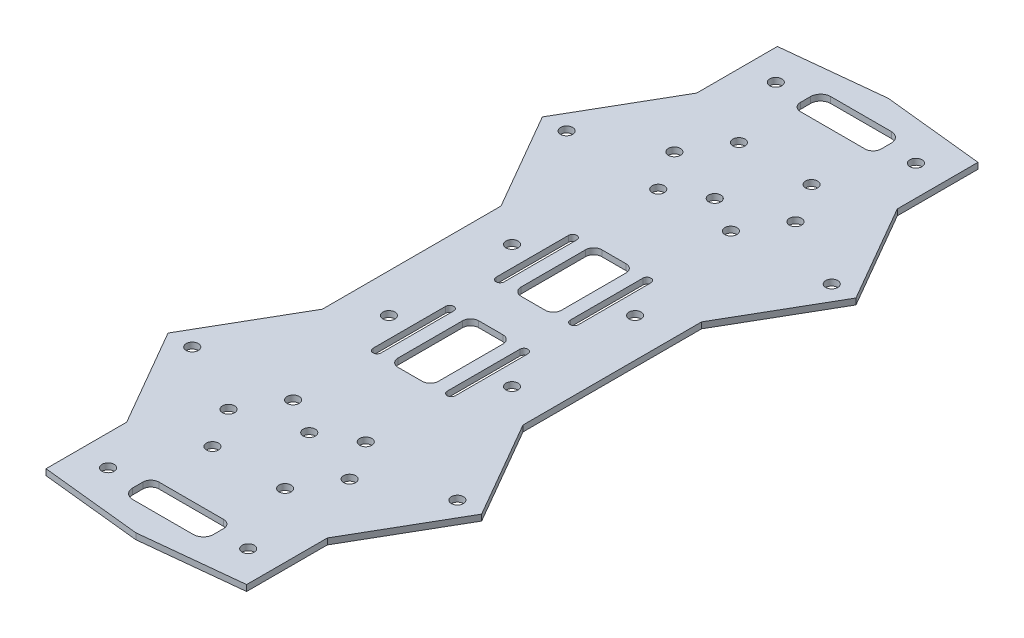
SolidWorks part; units mm, degrees
other "TopFrame"
ref_plane "Front Plane" through (0, 0, 0) normal (0, 0, 1) x (1, 0, 0)
ref_plane "Top Plane" through (0, 0, 0) normal (0, 1, 0) x (1, 0, 0)
ref_plane "Right Plane" through (0, 0, 0) normal (1, 0, 0) x (0, 0, -1)
sketch "Sketch1" plane through (0, 0, 0) normal (0, 1, 0) x (1, 0, 0)
  line L0 (-9.2, 6.25) -> (-9.2, 24.25) construction
  line L1 (-3, 5.25) -> (3, 5.25)
  line L2 (-5, 7.25) -> (-5, 23.25)
  line L3 (-3, 25.25) -> (3, 25.25)
  line L4 (5, 7.25) -> (5, 23.25)
  line L5 (-5, 5.25) -> (5, 25.25) construction
  line L6 (-5, 25.25) -> (5, 5.25) construction
  line L11 (-10.2, 6.25) -> (-10.2, 24.25)
  line L12 (-8.2, 6.25) -> (-8.2, 24.25)
  line L13 (0, 5.25) -> (0, 25.25) construction
  line L14 (9.2, 6.25) -> (9.2, 24.25) construction
  line L15 (10.2, 6.25) -> (10.2, 24.25)
  line L16 (8.2, 6.25) -> (8.2, 24.25)
  line L17 (-3, 0) -> (3, 0) construction
  line L18 (0, -5.25) -> (0, -25.25) construction
  line L19 (-5, -25.25) -> (5, -5.25) construction
  line L20 (-5, -5.25) -> (5, -25.25) construction
  line L21 (5, -7.25) -> (5, -23.25)
  line L22 (-3, -25.25) -> (3, -25.25)
  line L23 (-5, -7.25) -> (-5, -23.25)
  line L24 (-3, -5.25) -> (3, -5.25)
  line L25 (9.2, -6.25) -> (9.2, -24.25) construction
  line L26 (10.2, -6.25) -> (10.2, -24.25)
  line L27 (8.2, -6.25) -> (8.2, -24.25)
  line L28 (-9.2, -6.25) -> (-9.2, -24.25) construction
  line L29 (-10.2, -6.25) -> (-10.2, -24.25)
  line L30 (-8.2, -6.25) -> (-8.2, -24.25)
  line L31 (0, 93.25) -> (-24.863, 90.6368)
  line L32 (-24.863, 90.6368) -> (-24.863, 70.6368)
  line L33 (-24.863, 70.6368) -> (-38.863, 46.3881)
  line L34 (-38.863, 46.3881) -> (-24.863, 22.1394)
  line L35 (-24.863, 22.1394) -> (-24.863, -22.1394)
  line L36 (24.863, 22.1394) -> (24.863, -22.1394)
  line L37 (38.863, 46.3881) -> (24.863, 22.1394)
  line L38 (24.863, 70.6368) -> (38.863, 46.3881)
  line L39 (24.863, 90.6368) -> (24.863, 70.6368)
  line L40 (0, 93.25) -> (24.863, 90.6368)
  line L41 (0, -93.25) -> (24.863, -90.6368)
  line L42 (24.863, -90.6368) -> (24.863, -70.6368)
  line L43 (24.863, -70.6368) -> (38.863, -46.3881)
  line L44 (38.863, -46.3881) -> (24.863, -22.1394)
  line L45 (-38.863, -46.3881) -> (-24.863, -22.1394)
  line L46 (-24.863, -70.6368) -> (-38.863, -46.3881)
  line L47 (-24.863, -90.6368) -> (-24.863, -70.6368)
  line L48 (0, -93.25) -> (-24.863, -90.6368)
  arc A0 (-3, 5.25) -> (-5, 7.25) centre (-3, 7.25) cw
  arc A1 (3, 5.25) -> (5, 7.25) centre (3, 7.25) ccw
  arc A2 (3, 25.25) -> (5, 23.25) centre (3, 23.25) cw
  arc A3 (-5, 23.25) -> (-3, 25.25) centre (-3, 23.25) cw
  arc A4 (-10.2, 6.25) -> (-8.2, 6.25) centre (-9.2, 6.25) ccw
  arc A5 (-8.2, 24.25) -> (-10.2, 24.25) centre (-9.2, 24.25) ccw
  arc A6 (10.2, 6.25) -> (8.2, 6.25) centre (9.2, 6.25) cw
  arc A7 (8.2, 24.25) -> (10.2, 24.25) centre (9.2, 24.25) cw
  arc A8 (-5, -23.25) -> (-3, -25.25) centre (-3, -23.25) ccw
  arc A9 (3, -25.25) -> (5, -23.25) centre (3, -23.25) ccw
  arc A10 (3, -5.25) -> (5, -7.25) centre (3, -7.25) cw
  arc A11 (-3, -5.25) -> (-5, -7.25) centre (-3, -7.25) ccw
  arc A12 (10.2, -6.25) -> (8.2, -6.25) centre (9.2, -6.25) ccw
  arc A13 (8.2, -24.25) -> (10.2, -24.25) centre (9.2, -24.25) ccw
  arc A14 (-10.2, -6.25) -> (-8.2, -6.25) centre (-9.2, -6.25) cw
  arc A15 (-8.2, -24.25) -> (-10.2, -24.25) centre (-9.2, -24.25) cw
  circle A16 centre (0, 50.25) radius 1.5
  circle A17 centre (-9, 45.25) radius 1.5
  circle A18 centre (-15, 55.25) radius 1.5
  circle A19 centre (-9, 65.25) radius 1.5
  circle A20 centre (9, 45.25) radius 1.5
  circle A21 centre (9, 65.25) radius 1.5
  circle A22 centre (15, 55.25) radius 1.5
  circle A23 centre (-15.25, 15.25) radius 1.5
  circle A24 centre (15.25, 15.25) radius 1.5
  circle A25 centre (-32.863, 46.3881) radius 1.5
  circle A26 centre (-17.363, 82.75) radius 1.5
  circle A27 centre (32.863, 46.3881) radius 1.5
  circle A28 centre (17.363, 82.75) radius 1.5
  circle A29 centre (-15.25, -15.25) radius 1.5
  circle A30 centre (15.25, -15.25) radius 1.5
  circle A31 centre (32.863, -46.3881) radius 1.5
  circle A32 centre (9, -45.25) radius 1.5
  circle A33 centre (-32.863, -46.3881) radius 1.5
  circle A34 centre (-9, -45.25) radius 1.5
  circle A35 centre (15, -55.25) radius 1.5
  circle A36 centre (0, -50.25) radius 1.5
  circle A37 centre (-15, -55.25) radius 1.5
  circle A38 centre (-9, -65.25) radius 1.5
  circle A39 centre (9, -65.25) radius 1.5
  circle A40 centre (17.363, -82.75) radius 1.5
  circle A41 centre (-17.363, -82.75) radius 1.5
  point P0 (0, 15.25)
  point P19 (-9.2, 15.25)
  point P25 (-9.2, 25.25)
  point P26 (-9.2, 5.25)
  point P31 (9.2, 15.25)
  point P58 (9.2, -15.25)
  point P65 (-9.2, -15.25)
  point P70 (0, -15.25)
  point P83 (24.863, 0)
  point P84 (-24.863, 0)
  dimension "D4" = 2
  dimension "D6" = 1
  dimension "D15" = 3
  dimension "D16" = 25
  dimension "D17" = 20
  dimension "D18" = 9
  dimension "D19" = 10
  dimension "D21" = 10
  dimension "D23" = 3
  dimension "D24" = 3
  dimension "D25" = 3
  dimension "D26" = 30.5
  dimension "D27" = 3
  dimension "D28" = 6
  dimension "D29" = 3
  dimension "D30" = 7.5
  dimension "D31" = 3
  dimension "D32" = 57.5
  dimension "D33" = 30.5
  dimension "D1" = 10
  dimension "D2" = 20
  dimension "D3" = 5.25
  dimension "D5" = 20
  dimension "D7" = 3.2
  dimension "D8" = 25
  dimension "D9" = 68
  dimension "D10" = 20
  dimension "D11" = 96
  dimension "D12" = 28
  dimension "D13" = 150
  dimension "D14" = 120
  dimension "D20" = 6
  dimension "D22" = 6
extrude "Boss-Extrude1" add sketch "Sketch1" along normal blind 1.5
sketch "Sketch2" plane through (0, 1.5, 0) normal (0, 1, 0) x (1, 0, 0)
  line L0 (0, 0) -> (9, 0) construction
  line L1 (-8, 79.5) -> (8, 79.5)
  line L2 (-10, 81.5) -> (-10, 84)
  line L3 (-7.5, 86.5) -> (7.5, 86.5)
  line L4 (10, 81.5) -> (10, 84)
  line L5 (-10, 79.5) -> (10, 86.5) construction
  line L6 (-10, 86.5) -> (10, 79.5) construction
  line L7 (-10, -86.5) -> (10, -79.5) construction
  line L8 (-10, -79.5) -> (10, -86.5) construction
  line L9 (10, -81.5) -> (10, -84)
  line L10 (-7.5, -86.5) -> (7.5, -86.5)
  line L11 (-10, -81.5) -> (-10, -84)
  line L12 (-8, -79.5) -> (8, -79.5)
  arc A0 (8, 79.5) -> (10, 81.5) centre (8, 81.5) ccw
  arc A1 (-8, 79.5) -> (-10, 81.5) centre (-8, 81.5) cw
  arc A2 (7.5, 86.5) -> (10, 84) centre (7.5, 84) cw
  arc A3 (-10, 84) -> (-7.5, 86.5) centre (-7.5, 84) cw
  arc A4 (-10, -84) -> (-7.5, -86.5) centre (-7.5, -84) ccw
  arc A5 (7.5, -86.5) -> (10, -84) centre (7.5, -84) ccw
  arc A6 (-8, -79.5) -> (-10, -81.5) centre (-8, -81.5) ccw
  arc A7 (8, -79.5) -> (10, -81.5) centre (8, -81.5) cw
  point P0 (0, 83)
  point P36 (0, -83)
  dimension "D3" = 2
  dimension "D5" = 2.5
  dimension "D1" = 20
  dimension "D2" = 7
  dimension "D4" = 79.5
extrude "Cut-Extrude1" cut sketch "Sketch2" against normal up to surface (1.5 mm away) up to face at (17.363, 0, 84.25)
